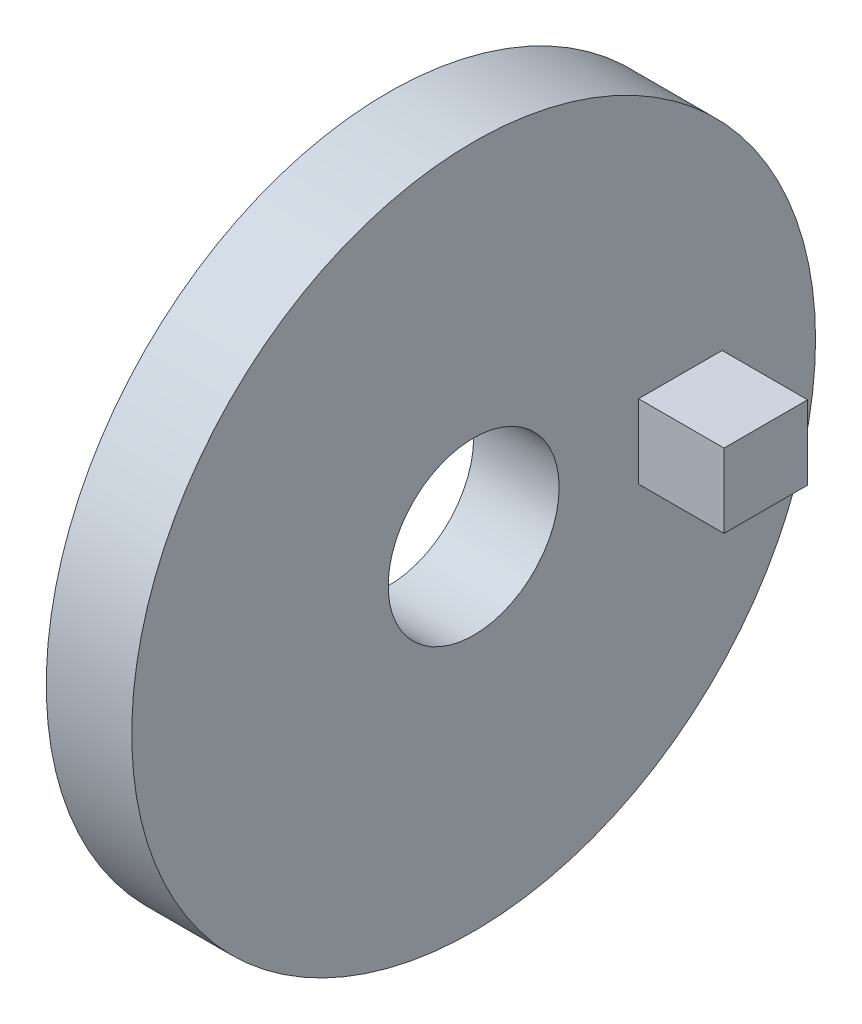
SolidWorks part; units mm, degrees
ref_plane "前视基准面" through (0, 0, 0) normal (0, 0, 1) x (1, 0, 0)
ref_plane "上视基准面" through (0, 0, 0) normal (0, 1, 0) x (1, 0, 0)
ref_plane "右视基准面" through (0, 0, 0) normal (1, 0, 0) x (0, 0, -1)
other "Configuration Table"
sketch "草图1" plane through (0, 0, 0) normal (1, 0, 0) x (0, 0, -1)
  circle A0 centre (0, 0) radius 10
  circle A1 centre (0, 0) radius 40
extrude "凸台-拉伸1" add sketch "草图1" along normal blind 10
sketch "草图2" plane through (10, 0, 0) normal (1, 0, 0) x (0, 0, -1)
  line L1 (19.2924, 4.3248) -> (29.0703, 4.3248)
  line L2 (19.2924, 4.3248) -> (19.2924, -4.3248)
  line L3 (19.2924, -4.3248) -> (29.0703, -4.3248)
  line L4 (29.0703, 4.3248) -> (29.0703, -4.3248)
  line L5 (19.2924, 4.3248) -> (29.0703, -4.3248) construction
  line L6 (19.2924, -4.3248) -> (29.0703, 4.3248) construction
  point P0 (24.1813, 0)
extrude "凸台-拉伸2" add sketch "草图2" along normal blind 10
